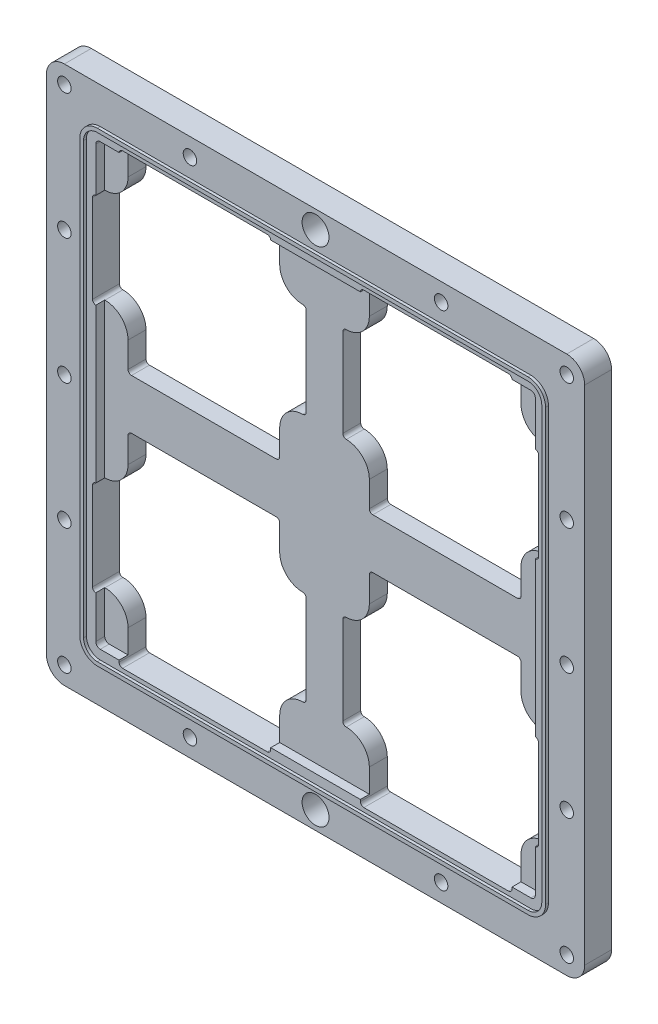
SolidWorks part; units mm, degrees
ref_plane "Front Plane" through (0, 0, 0) normal (0, 0, 1) x (1, 0, 0)
ref_plane "Top Plane" through (0, 0, 0) normal (0, 1, 0) x (1, 0, 0)
ref_plane "Right Plane" through (0, 0, 0) normal (1, 0, 0) x (0, 0, -1)
sketch "Sketch1" plane through (0, 0, 0) normal (0, 0, 1) x (1, 0, 0)
  line L1 (0, 0) -> (190.5, 0)
  line L2 (0, 0) -> (0, 190.5)
  line L3 (0, 190.5) -> (190.5, 190.5)
  line L4 (190.5, 0) -> (190.5, 190.5)
  dimension "D1" = 190.5
  dimension "D2" = 190.5
extrude "Boss-Extrude1" add sketch "Sketch1" along normal blind 9.525
sketch "Sketch4" plane through (0, 0, 9.525) normal (0, 0, 1) x (1, 0, 0)
  line L3 (0, 190.5) -> (0, 0) construction
  line L4 (6.35, 184.15) -> (184.15, 184.15) construction
  line L5 (6.35, 184.15) -> (6.35, 6.35) construction
  line L6 (6.35, 6.35) -> (184.15, 6.35) construction
  line L7 (184.15, 184.15) -> (184.15, 6.35) construction
  line L8 (190.5, 190.5) -> (0, 190.5) construction
  line L9 (190.5, 0) -> (190.5, 190.5) construction
  line L10 (0, 0) -> (190.5, 0) construction
  circle A0 centre (6.35, 6.35) radius 2.3813
  circle A1 centre (6.35, 184.15) radius 2.3813
  circle A2 centre (184.15, 184.15) radius 2.3813
  circle A3 centre (184.15, 6.35) radius 2.3813
  dimension "D5" = 4.7625
  dimension "D1" = 6.35
  dimension "D2" = 6.35
  dimension "D3" = 6.35
  dimension "D4" = 6.35
extrude "Cut-Extrude1" cut sketch "Sketch4" against normal through all
sketch "Sketch5" plane through (0, 0, 9.525) normal (0, 0, 1) x (1, 0, 0)
  line L0 (0, 190.5) -> (0, 0) construction
  line L1 (19.05, 177.8) -> (171.45, 177.8) construction
  line L2 (12.7, 171.45) -> (12.7, 19.05) construction
  line L3 (19.05, 12.7) -> (171.45, 12.7) construction
  line L4 (177.8, 171.45) -> (177.8, 19.05) construction
  line L5 (190.5, 190.5) -> (0, 190.5) construction
  line L6 (190.5, 0) -> (190.5, 190.5) construction
  line L7 (0, 0) -> (190.5, 0) construction
  line L8 (19.05, 14.2875) -> (171.45, 14.2875) construction
  line L9 (14.2875, 171.45) -> (14.2875, 19.05) construction
  line L10 (19.05, 176.2125) -> (171.45, 176.2125) construction
  line L11 (176.2125, 171.45) -> (176.2125, 19.05) construction
  line L12 (12.827, 171.45) -> (12.827, 19.05)
  line L13 (19.05, 177.673) -> (171.45, 177.673)
  line L14 (177.673, 171.45) -> (177.673, 19.05)
  line L15 (19.05, 12.827) -> (171.45, 12.827)
  line L16 (176.3395, 171.45) -> (176.3395, 19.05)
  line L17 (19.05, 176.3395) -> (171.45, 176.3395)
  line L18 (14.1605, 171.45) -> (14.1605, 19.05)
  line L19 (19.05, 14.1605) -> (171.45, 14.1605)
  arc A0 (171.45, 12.7) -> (177.8, 19.05) centre (171.45, 19.05) ccw construction
  arc A1 (12.7, 19.05) -> (19.05, 12.7) centre (19.05, 19.05) ccw construction
  arc A2 (171.45, 177.8) -> (177.8, 171.45) centre (171.45, 171.45) cw construction
  arc A3 (19.05, 177.8) -> (12.7, 171.45) centre (19.05, 171.45) ccw construction
  arc A4 (14.2875, 19.05) -> (19.05, 14.2875) centre (19.05, 19.05) ccw construction
  arc A5 (19.05, 176.2125) -> (14.2875, 171.45) centre (19.05, 171.45) ccw construction
  arc A6 (171.45, 176.2125) -> (176.2125, 171.45) centre (171.45, 171.45) cw construction
  arc A7 (171.45, 14.2875) -> (176.2125, 19.05) centre (171.45, 19.05) ccw construction
  arc A8 (19.05, 177.673) -> (12.827, 171.45) centre (19.05, 171.45) ccw
  arc A9 (171.45, 177.673) -> (177.673, 171.45) centre (171.45, 171.45) cw
  arc A10 (171.45, 12.827) -> (177.673, 19.05) centre (171.45, 19.05) ccw
  arc A11 (12.827, 19.05) -> (19.05, 12.827) centre (19.05, 19.05) ccw
  arc A12 (171.45, 176.3395) -> (176.3395, 171.45) centre (171.45, 171.45) cw
  arc A13 (19.05, 176.3395) -> (14.1605, 171.45) centre (19.05, 171.45) ccw
  arc A14 (14.1605, 19.05) -> (19.05, 14.1605) centre (19.05, 19.05) ccw
  arc A15 (171.45, 14.1605) -> (176.3395, 19.05) centre (171.45, 19.05) ccw
  dimension "D5" = 6.35
  dimension "D1" = 12.7
  dimension "D2" = 12.7
  dimension "D3" = 12.7
  dimension "D4" = 12.7
  dimension "D6" = 1.5875
  dimension "D7" = 1.5875
  dimension "D8" = 0.127
  dimension "D9" = 0.127
  dimension "D10" = 0.127
sketch "Sketch6" plane through (0, 0, 9.525) normal (0, 0, 1) x (1, 0, 0)
  line L24 (171.45, 173.0375) -> (19.05, 173.0375)
  line L25 (173.0375, 19.05) -> (173.0375, 171.45)
  line L26 (19.05, 17.4625) -> (171.45, 17.4625)
  line L27 (17.4625, 171.45) -> (17.4625, 19.05)
  line L28 (171.45, 173.0375) -> (19.05, 173.0375)
  line L29 (173.0375, 19.05) -> (173.0375, 171.45)
  line L30 (19.05, 17.4625) -> (171.45, 17.4625)
  line L31 (17.4625, 171.45) -> (17.4625, 19.05)
  arc A20 (19.05, 173.0375) -> (17.4625, 171.45) centre (19.05, 171.45) ccw
  arc A21 (173.0375, 171.45) -> (171.45, 173.0375) centre (171.45, 171.45) ccw
  arc A22 (171.45, 17.4625) -> (173.0375, 19.05) centre (171.45, 19.05) ccw
  arc A23 (17.4625, 19.05) -> (19.05, 17.4625) centre (19.05, 19.05) ccw
  arc A24 (19.05, 173.0375) -> (17.4625, 171.45) centre (19.05, 171.45) ccw
  arc A25 (173.0375, 171.45) -> (171.45, 173.0375) centre (171.45, 171.45) ccw
  arc A26 (171.45, 17.4625) -> (173.0375, 19.05) centre (171.45, 19.05) ccw
  arc A27 (17.4625, 19.05) -> (19.05, 17.4625) centre (19.05, 19.05) ccw
  dimension "D1" = 3.175
extrude "Cut-Extrude3" cut sketch "Sketch6" against normal blind 3.175
extrude "Boss-Extrude2" add sketch "Sketch5" along normal blind 1.016 contours L12 A11 L15 A10 L14 A9 L13 A8 A15 L19 A14 L18 A13 L17 A12 L16
pattern_linear "LPattern2" count 4 spacing 44.45 along (0, -1, 0) of "Cut-Extrude1"
pattern_linear "LPattern3" count 4 spacing 44.45 along (1, 0, 0) of "Cut-Extrude1"
sketch "Sketch7" plane through (0, 0, 9.525) normal (0, 0, 1) x (1, 0, 0)
  circle A0 centre (95.25, 6.35) radius 4.7625
  circle A1 centre (95.25, 184.15) radius 4.7625
  circle A2 centre (95.25, 184.15) radius 2.3813 construction
  circle A3 centre (95.25, 6.35) radius 2.3813 construction
  dimension "D1" = 9.525
extrude "Cut-Extrude4" cut sketch "Sketch7" against normal through all
fillet "Fillet1" radius 6.35 4 edges at (0, 190.5, 4.7625) (190.5, 190.5, 4.7625) (0, 0, 4.7625) (190.5, 0, 4.7625)
sketch "Sketch8" plane through (0, 0, 0) normal (0, 0, -1) x (-1, 0, 0)
  line L0 (-175.768, 154.559) -> (-175.768, 123.3678)
  line L1 (-166.37, 113.9698) -> (-166.37, 104.9782)
  line L2 (-163.5506, 102.1588) -> (-112.3442, 102.1588)
  line L3 (-109.5248, 104.9782) -> (-109.5248, 113.9698)
  line L4 (-100.1268, 123.3678) -> (-100.1268, 154.559)
  line L5 (-109.5248, 163.957) -> (-109.5248, 172.9486)
  line L6 (-112.3442, 175.768) -> (-163.5506, 175.768)
  line L7 (-166.37, 172.9486) -> (-166.37, 163.957)
  line L8 (-172.9486, 175.768) -> (-172.9486, 102.1588) construction
  line L9 (-175.768, 172.9486) -> (-100.1268, 172.9486) construction
  line L10 (-175.768, 175.768) -> (-100.1268, 175.768) construction
  line L11 (-175.768, 175.768) -> (-175.768, 102.1588) construction
  line L12 (-175.768, 102.1588) -> (-100.1268, 102.1588) construction
  line L13 (-100.1268, 175.768) -> (-100.1268, 102.1588) construction
  line L14 (-175.768, 163.957) -> (-100.1268, 163.957) construction
  line L15 (-175.768, 154.559) -> (-100.1268, 154.559) construction
  line L16 (-175.768, 123.3678) -> (-100.1268, 123.3678) construction
  line L17 (-175.768, 113.9698) -> (-100.1268, 113.9698) construction
  line L18 (-175.768, 104.9782) -> (-100.1268, 104.9782) construction
  line L19 (-166.37, 102.1588) -> (-166.37, 175.768) construction
  line L20 (-163.5506, 175.768) -> (-163.5506, 102.1588) construction
  line L21 (-112.3442, 175.768) -> (-112.3442, 102.1588) construction
  line L22 (-109.5248, 175.768) -> (-109.5248, 102.1588) construction
  line L23 (-102.9462, 102.1588) -> (-102.9462, 175.768) construction
  line L24 (-100.1268, 157.3784) -> (-175.768, 157.3784) construction
  line L27 (-112.3442, 177.8) -> (-163.5506, 177.8)
  line L28 (-168.402, 172.9486) -> (-168.402, 163.957)
  line L29 (-177.8, 154.559) -> (-177.8, 123.3678)
  line L30 (-168.402, 113.9698) -> (-168.402, 104.9782)
  line L31 (-163.5506, 100.1268) -> (-112.3442, 100.1268)
  line L32 (-107.4928, 104.9782) -> (-107.4928, 113.9698)
  line L33 (-98.0948, 123.3678) -> (-98.0948, 154.559)
  line L34 (-107.4928, 163.957) -> (-107.4928, 172.9486)
  line L35 (-184.15, 190.5) -> (-6.35, 190.5) construction
  line L36 (-190.5, 6.35) -> (-190.5, 184.15) construction
  arc A0 (-172.9486, 157.3784) -> (-166.37, 163.957) centre (-172.9486, 163.957) ccw
  arc A1 (-172.9486, 157.3784) -> (-175.768, 154.559) centre (-172.9486, 154.559) ccw
  arc A2 (-175.768, 123.3678) -> (-172.9486, 120.5484) centre (-172.9486, 123.3678) ccw
  arc A3 (-166.37, 113.9698) -> (-172.9486, 120.5484) centre (-172.9486, 113.9698) ccw
  arc A4 (-166.37, 104.9782) -> (-163.5506, 102.1588) centre (-163.5506, 104.9782) ccw
  arc A5 (-112.3442, 102.1588) -> (-109.5248, 104.9782) centre (-112.3442, 104.9782) ccw
  arc A6 (-102.9462, 120.5484) -> (-109.5248, 113.9698) centre (-102.9462, 113.9698) ccw
  arc A7 (-102.9462, 120.5484) -> (-100.1268, 123.3678) centre (-102.9462, 123.3678) ccw
  arc A8 (-100.1268, 154.559) -> (-102.9462, 157.3784) centre (-102.9462, 154.559) ccw
  arc A9 (-109.5248, 163.957) -> (-102.9462, 157.3784) centre (-102.9462, 163.957) ccw
  arc A10 (-109.5248, 172.9486) -> (-112.3442, 175.768) centre (-112.3442, 172.9486) ccw
  arc A11 (-163.5506, 175.768) -> (-166.37, 172.9486) centre (-163.5506, 172.9486) ccw
  arc A12 (-163.5506, 177.8) -> (-168.402, 172.9486) centre (-163.5506, 172.9486) ccw
  arc A13 (-172.9486, 159.4104) -> (-168.402, 163.957) centre (-172.9486, 163.957) ccw
  arc A14 (-172.9486, 159.4104) -> (-177.8, 154.559) centre (-172.9486, 154.559) ccw
  arc A15 (-177.8, 123.3678) -> (-172.9486, 118.5164) centre (-172.9486, 123.3678) ccw
  arc A16 (-168.402, 113.9698) -> (-172.9486, 118.5164) centre (-172.9486, 113.9698) ccw
  arc A17 (-168.402, 104.9782) -> (-163.5506, 100.1268) centre (-163.5506, 104.9782) ccw
  arc A18 (-112.3442, 100.1268) -> (-107.4928, 104.9782) centre (-112.3442, 104.9782) ccw
  arc A19 (-102.9462, 118.5164) -> (-107.4928, 113.9698) centre (-102.9462, 113.9698) ccw
  arc A20 (-102.9462, 118.5164) -> (-98.0948, 123.3678) centre (-102.9462, 123.3678) ccw
  arc A21 (-98.0948, 154.559) -> (-102.9462, 159.4104) centre (-102.9462, 154.559) ccw
  arc A22 (-107.4928, 163.957) -> (-102.9462, 159.4104) centre (-102.9462, 163.957) ccw
  arc A23 (-107.4928, 172.9486) -> (-112.3442, 177.8) centre (-112.3442, 172.9486) ccw
  dimension "D4" = 11.811
  dimension "D5" = 21.209
  dimension "D6" = 52.4002
  dimension "D1" = 73.6092
  dimension "D2" = 75.6412
  dimension "D3" = 2.8194
  dimension "D7" = 61.7982
  dimension "D8" = 70.7898
  dimension "D9" = 2.8194
  dimension "D10" = 9.398
  dimension "D11" = 12.2174
  dimension "D12" = 63.4238
  dimension "D13" = 66.2432
  dimension "D14" = 72.8218
  dimension "D15" = 55.2196
  dimension "D16" = 12.7
  dimension "D17" = 12.7
  dimension "D18" = 2.032
extrude "Cut-Extrude5" cut sketch "Sketch8" against normal blind 3.175
sketch "Sketch10" plane through (0, 0, 0) normal (0, 0, -1) x (-1, 0, 0)
  line L18 (-174.1805, 154.559) -> (-174.1805, 123.3678)
  line L19 (-164.7825, 113.9698) -> (-164.7825, 104.9782)
  line L20 (-163.5506, 103.7463) -> (-112.3442, 103.7463)
  line L21 (-111.1123, 104.9782) -> (-111.1123, 113.9698)
  line L22 (-101.7143, 123.3678) -> (-101.7143, 154.559)
  line L23 (-111.1123, 163.957) -> (-111.1123, 172.9486)
  line L24 (-112.3442, 174.1805) -> (-163.5506, 174.1805)
  line L25 (-164.7825, 172.9486) -> (-164.7825, 163.957)
  line L26 (-174.1805, 154.559) -> (-174.1805, 123.3678)
  line L27 (-164.7825, 113.9698) -> (-164.7825, 104.9782)
  line L28 (-163.5506, 103.7463) -> (-112.3442, 103.7463)
  line L29 (-111.1123, 104.9782) -> (-111.1123, 113.9698)
  line L30 (-101.7143, 123.3678) -> (-101.7143, 154.559)
  line L31 (-111.1123, 163.957) -> (-111.1123, 172.9486)
  line L32 (-112.3442, 174.1805) -> (-163.5506, 174.1805)
  line L33 (-164.7825, 172.9486) -> (-164.7825, 163.957)
  arc A28 (-172.9486, 155.7909) -> (-174.1805, 154.559) centre (-172.9486, 154.559) ccw
  arc A29 (-174.1805, 123.3678) -> (-172.9486, 122.1359) centre (-172.9486, 123.3678) ccw
  arc A30 (-164.7825, 113.9698) -> (-172.9486, 122.1359) centre (-172.9486, 113.9698) ccw
  arc A31 (-164.7825, 104.9782) -> (-163.5506, 103.7463) centre (-163.5506, 104.9782) ccw
  arc A32 (-112.3442, 103.7463) -> (-111.1123, 104.9782) centre (-112.3442, 104.9782) ccw
  arc A33 (-102.9462, 122.1359) -> (-111.1123, 113.9698) centre (-102.9462, 113.9698) ccw
  arc A34 (-102.9462, 122.1359) -> (-101.7143, 123.3678) centre (-102.9462, 123.3678) ccw
  arc A35 (-101.7143, 154.559) -> (-102.9462, 155.7909) centre (-102.9462, 154.559) ccw
  arc A36 (-111.1123, 163.957) -> (-102.9462, 155.7909) centre (-102.9462, 163.957) ccw
  arc A37 (-111.1123, 172.9486) -> (-112.3442, 174.1805) centre (-112.3442, 172.9486) ccw
  arc A38 (-163.5506, 174.1805) -> (-164.7825, 172.9486) centre (-163.5506, 172.9486) ccw
  arc A39 (-172.9486, 155.7909) -> (-164.7825, 163.957) centre (-172.9486, 163.957) ccw
  arc A40 (-172.9486, 155.7909) -> (-174.1805, 154.559) centre (-172.9486, 154.559) ccw
  arc A41 (-174.1805, 123.3678) -> (-172.9486, 122.1359) centre (-172.9486, 123.3678) ccw
  arc A42 (-164.7825, 113.9698) -> (-172.9486, 122.1359) centre (-172.9486, 113.9698) ccw
  arc A43 (-164.7825, 104.9782) -> (-163.5506, 103.7463) centre (-163.5506, 104.9782) ccw
  arc A44 (-112.3442, 103.7463) -> (-111.1123, 104.9782) centre (-112.3442, 104.9782) ccw
  arc A45 (-102.9462, 122.1359) -> (-111.1123, 113.9698) centre (-102.9462, 113.9698) ccw
  arc A46 (-102.9462, 122.1359) -> (-101.7143, 123.3678) centre (-102.9462, 123.3678) ccw
  arc A47 (-101.7143, 154.559) -> (-102.9462, 155.7909) centre (-102.9462, 154.559) ccw
  arc A48 (-111.1123, 163.957) -> (-102.9462, 155.7909) centre (-102.9462, 163.957) ccw
  arc A49 (-111.1123, 172.9486) -> (-112.3442, 174.1805) centre (-112.3442, 172.9486) ccw
  arc A50 (-163.5506, 174.1805) -> (-164.7825, 172.9486) centre (-163.5506, 172.9486) ccw
  arc A51 (-172.9486, 155.7909) -> (-164.7825, 163.957) centre (-172.9486, 163.957) ccw
  dimension "D1" = 1.5875
extrude "Cut-Extrude6" cut sketch "Sketch10" against normal through all
sketch "Sketch11" plane through (0, 0, 0) normal (0, 0, -1) x (-1, 0, 0)
  line L0 (-137.9474, 172.9994) -> (-137.9474, 177.8) construction
  line L1 (-172.9486, 172.9994) -> (-102.9462, 172.9994) construction
  line L2 (-172.9486, 172.9994) -> (-172.9486, 104.9274) construction
  line L3 (-172.9486, 104.9274) -> (-102.9462, 104.9274) construction
  line L4 (-102.9462, 172.9994) -> (-102.9462, 104.9274) construction
  line L5 (-112.3442, 177.8) -> (-163.5506, 177.8) construction
  line L6 (-137.9474, 104.9274) -> (-137.9474, 100.1268) construction
  line L7 (-163.5506, 100.1268) -> (-112.3442, 100.1268) construction
  line L8 (-172.9486, 138.9634) -> (-177.8, 138.9634) construction
  line L9 (-177.8, 154.559) -> (-177.8, 123.3678) construction
  line L10 (-102.9462, 138.9634) -> (-98.0948, 138.9634) construction
  line L11 (-98.0948, 123.3678) -> (-98.0948, 154.559) construction
  circle A0 centre (-172.9486, 172.9994) radius 1.3462
  circle A1 centre (-102.9462, 172.9994) radius 1.3462
  circle A2 centre (-102.9462, 104.9274) radius 1.3462
  circle A3 centre (-172.9486, 104.9274) radius 1.3462
  dimension "D3" = 2.6924
  dimension "D1" = 70.0024
  dimension "D2" = 68.072
extrude "Cut-Extrude7" cut sketch "Sketch11" against normal blind 4.7625
pattern_linear "LPattern1" count 2 spacing 85.3948 along (-1, 0, 0) count 2 spacing 88.1634 along (0, -1, 0) of "Cut-Extrude6", "Cut-Extrude5", "Cut-Extrude7"
